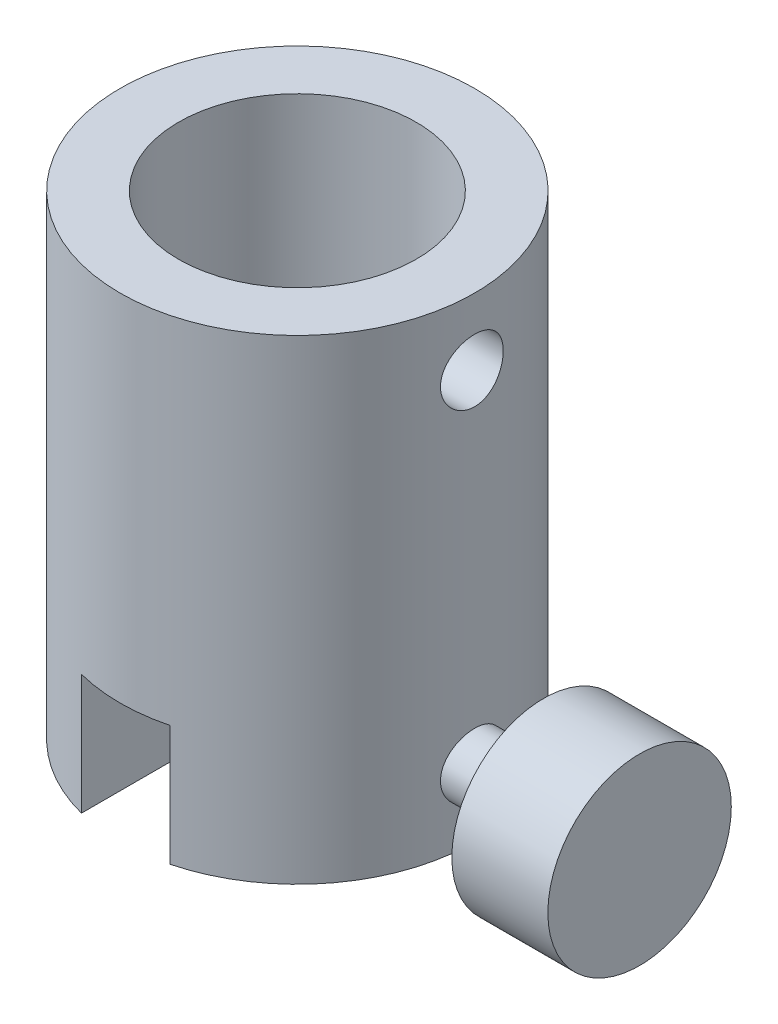
SolidWorks part; units mm, degrees
ref_plane "Front Plane" through (0, 0, 0) normal (0, 0, 1) x (1, 0, 0)
ref_plane "Top Plane" through (0, 0, 0) normal (0, 1, 0) x (1, 0, 0)
ref_plane "Right Plane" through (0, 0, 0) normal (1, 0, 0) x (0, 0, -1)
sketch "Sketch1" plane through (0, 0, 0) normal (0, 1, 0) x (1, 0, 0)
  circle A0 centre (0, 0) radius 9.4742
  dimension "D1" = 18.9484
extrude "Boss-Extrude1" add sketch "Sketch1" along normal blind 25.4
sketch "Sketch2" plane through (0, 25.4, 0) normal (0, 1, 0) x (1, 0, 0)
  circle A0 centre (0, 0) radius 6.35
  dimension "D1" = 12.7
extrude "Cut-Extrude1" cut sketch "Sketch2" against normal blind 15.9766
sketch "Sketch3" plane through (0, 0, 0) normal (0, 0, 1) x (1, 0, 0)
  line L0 (0, 0) -> (2.3622, 0)
  line L1 (-9.4742, 0) -> (9.4742, 0) construction
  line L2 (0, 0) -> (-2.3622, 0)
  line L3 (-2.3622, 0) -> (-2.3622, 6.4262)
  line L4 (-2.3622, 6.4262) -> (2.3622, 6.4262)
  line L5 (2.3622, 6.4262) -> (2.3622, 0)
  dimension "D1" = 6.4262
  dimension "D2" = 4.7244
extrude "Cut-Extrude2" cut sketch "Sketch3" against normal through all and the other way through all
sketch "Sketch4" plane through (0, 0, 0) normal (1, 0, 0) x (0, 0, -1)
  circle A0 centre (0, 3.5814) radius 1.6764
  dimension "D2" = 3.3528
  dimension "D1" = 3.5814
extrude "Cut-Extrude3" cut sketch "Sketch4" against normal through all and the other way through all
sketch "Sketch5" plane through (0, 0, 0) normal (1, 0, 0) x (0, 0, -1)
  line L0 (6.35, 25.4) -> (-6.35, 25.4) construction
  circle A0 centre (0, 21.8186) radius 1.6764
  dimension "D2" = 3.3528
  dimension "D1" = 3.5814
extrude "Cut-Extrude4" cut sketch "Sketch5" along normal through all
ref_plane "Plane1" through (9.4742, 0, 0) normal (1, 0, 0) x (0, 0, -1)
sketch "Sketch6" plane through (9.4742, 0, 0) normal (1, 0, 0) x (0, 0, -1)
  circle A0 centre (0, 3.5814) radius 1.6764 construction
  circle A1 centre (0, 3.5814) radius 1.6764
extrude "Boss-Extrude2" add sketch "Sketch6" along normal blind 3.683 separate body
sketch "Sketch7" plane through (13.1572, 0, 0) normal (1, 0, 0) x (0, 0, -1)
  circle A0 centre (0, 3.5814) radius 4.9022
  dimension "D1" = 9.8044
extrude "Boss-Extrude3" add sketch "Sketch7" along normal blind 5.1308
sketch "Sketch8" plane through (9.4742, 0, 0) normal (1, 0, 0) x (0, 0, -1)
  circle A0 centre (0, 3.5814) radius 1.6764 construction
  circle A1 centre (0, 3.5814) radius 1.6764
extrude "Boss-Extrude4" add sketch "Sketch8" against normal blind 6.5278
